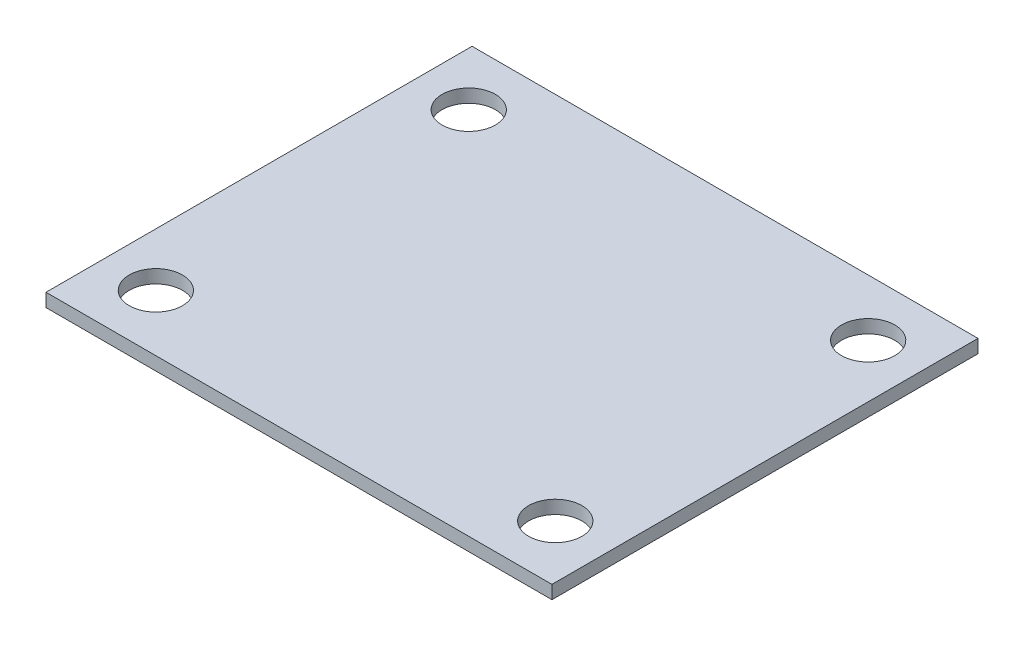
SolidWorks part; units mm, degrees
ref_plane "Front Plane" through (0, 0, 0) normal (0, 0, 1) x (1, 0, 0)
ref_plane "Top Plane" through (0, 0, 0) normal (0, 1, 0) x (1, 0, 0)
ref_plane "Right Plane" through (0, 0, 0) normal (1, 0, 0) x (0, 0, -1)
sketch "Sketch1" plane through (0, 0, 0) normal (0, 1, 0) x (1, 0, 0)
  line L1 (-19, 16) -> (19, 16)
  line L2 (-19, 16) -> (-19, -16)
  line L3 (-19, -16) -> (19, -16)
  line L4 (19, 16) -> (19, -16)
  dimension "D1" = 38
  dimension "D2" = 32
  dimension "D3" = 16
  dimension "D4" = 19
extrude "Boss-Extrude1" add sketch "Sketch1" along normal blind 1
sketch "Sketch2" plane through (0, 1, 0) normal (0, 1, 0) x (1, 0, 0)
  circle A0 centre (15, -11.75) radius 2
  dimension "D1" = 4
  dimension "D2" = 15
  dimension "D3" = 11.75
extrude "Cut-Extrude1" cut sketch "Sketch2" against normal blind 1
mirror "Mirror1" about plane through (0, 0, 0) normal (1, 0, 0) of "Cut-Extrude1"
mirror "Mirror2" about plane through (0, 0, 0) normal (0, 0, 1) of "Mirror1", "Cut-Extrude1"
sketch "Sketch3" plane through (0, 0, 0) normal (0, -1, 0) x (1, 0, 0)
  circle A0 centre (0, 0) radius 15
  dimension "D1" = 30
ref_plane "Plane1" through (0, -2, 0) normal (0, -1, 0) x (1, 0, 0)
sketch "Sketch4" plane through (0, -2, 0) normal (0, -1, 0) x (1, 0, 0)
  circle A0 centre (0, 0) radius 12
  dimension "D1" = 24
loft "Loft1" add profiles "Sketch3", "Sketch4"
sketch "Sketch5" plane through (0, -2, 0) normal (0, -1, 0) x (1, 0, 0)
  circle A0 centre (0, 0) radius 9
  dimension "D1" = 18
extrude "Boss-Extrude2" add sketch "Sketch5" along normal blind 1
sketch "Sketch6" plane through (0, 1, 0) normal (0, 1, 0) x (1, 0, 0)
  circle A0 centre (0, 0) radius 3.5
  dimension "D1" = 7
